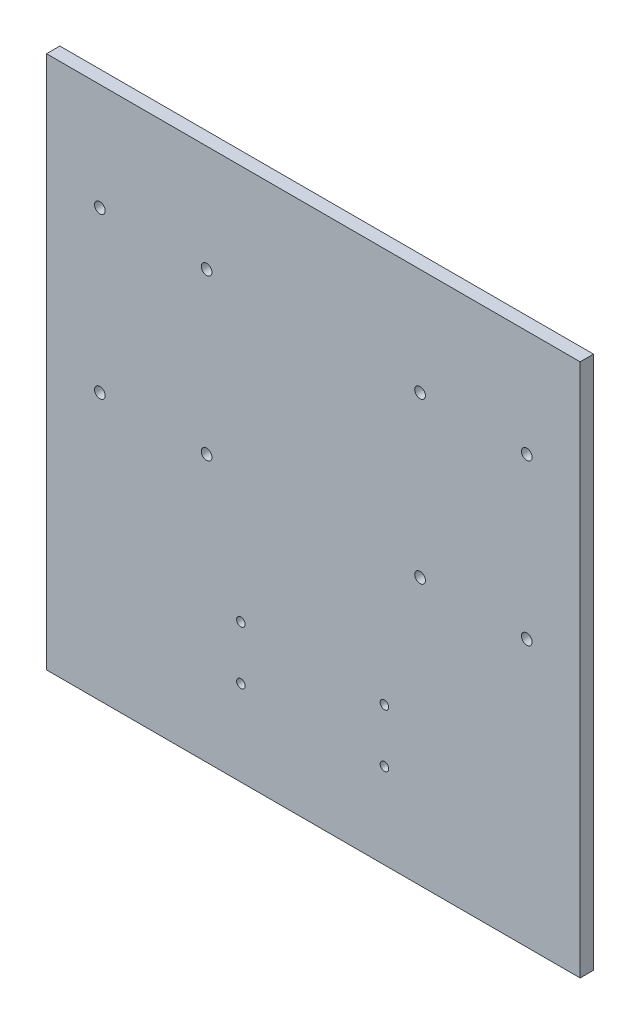
SolidWorks part; units mm, degrees
ref_plane "Plan de face" through (0, 0, 0) normal (0, 0, 1) x (1, 0, 0)
ref_plane "Plan de dessus" through (0, 0, 0) normal (0, 1, 0) x (1, 0, 0)
ref_plane "Plan de droite" through (0, 0, 0) normal (1, 0, 0) x (0, 0, -1)
sketch "Esquisse1" plane through (0, 0, 0) normal (0, 0, 1) x (1, 0, 0)
  line L1 (-100, 100) -> (100, 100)
  line L2 (-100, 100) -> (-100, -100)
  line L3 (-100, -100) -> (100, -100)
  line L4 (100, 100) -> (100, -100)
  line L5 (-100, 100) -> (100, -100) construction
  line L6 (-100, -100) -> (100, 100) construction
  point P0 (0, 0)
  dimension "D1" = 200
  dimension "D2" = 200
extrude "Boss.-Extru.1" add sketch "Esquisse1" along normal blind 5
sketch "Esquisse8" plane through (0, 0, 5) normal (0, 0, 1) x (1, 0, 0)
  circle A1 centre (-27.15, -68) radius 1.6
  circle A2 centre (-27.15, -68) radius 1.6
  circle A3 centre (-27.15, -48) radius 1.6
  circle A4 centre (-27.15, -48) radius 1.6
  circle A5 centre (26.65, -48) radius 1.6
  circle A6 centre (26.65, -48) radius 1.6
  circle A7 centre (26.65, -68) radius 1.6
  circle A8 centre (26.65, -68) radius 1.6
  dimension "D1" = 0
  dimension "D2" = 0
  dimension "D3" = 0
  dimension "D4" = 0
extrude "Enlèv. mat.-Extru.2" cut sketch "Esquisse8" against normal through all
sketch "Esquisse10" plane through (0, 0, 5) normal (0, 0, 1) x (1, 0, 0)
  line L0 (-100, 100) -> (-100, -100) construction
  line L1 (-103.8171, 30) -> (-12.967, 30) construction
  line L4 (0, 56.4955) -> (0, 15.9883) construction
  circle A0 centre (-80, 60) radius 2
  circle A1 centre (-40, 60) radius 2
  circle A2 centre (-40, 0) radius 2
  circle A3 centre (-80, 0) radius 2
  circle A4 centre (80, 0) radius 2
  circle A5 centre (40, 0) radius 2
  circle A6 centre (40, 60) radius 2
  circle A7 centre (80, 60) radius 2
  dimension "D2" = 4
  dimension "D3" = 4
  dimension "D1" = 40
  dimension "D4" = 20
  dimension "D5" = 60
  dimension "D6" = 60
  dimension "D7" = 30
extrude "Enlèv. mat.-Extru.4" cut sketch "Esquisse10" against normal through all
